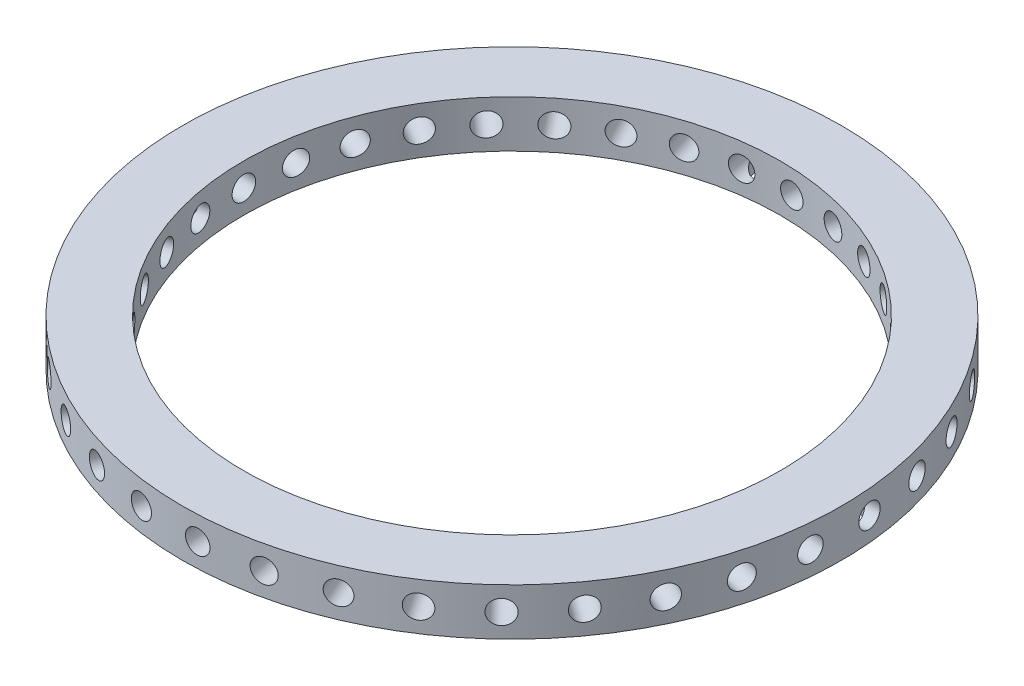
SolidWorks part; units mm, degrees
material "ABS"
ref_plane "Alzado" through (0, 0, 0) normal (0, 0, 1) x (1, 0, 0)
ref_plane "Planta" through (0, 0, 0) normal (0, 1, 0) x (1, 0, 0)
ref_plane "Vista lateral" through (0, 0, 0) normal (1, 0, 0) x (0, 0, -1)
sketch "Croquis1" plane through (0, 0, 0) normal (0, 0, 1) x (1, 0, 0)
  line L0 (0, 0) -> (-22.8, 0) construction
  line L1 (-22.8, 0) -> (-28, 0)
  line L2 (-28, 0) -> (-28, 1)
  line L3 (-28, 1) -> (-28, 4)
  line L4 (-22.8, 0) -> (-22.8, 4)
  line L5 (-22.8, 4) -> (-28, 4)
  line L6 (0, 0) -> (0, 7.1054) construction
  dimension "D1" = 22.8
  dimension "D2" = 28
  dimension "D3" = 1
  dimension "D4" = 3
revolve "Revolución1" add sketch "Croquis1" angle 360 about L6
ref_plane "Plano1" through (-28, 0, 0) normal (-1, 0, 0) x (0, 0, 1)
sketch "Croquis2" plane through (-28, 0, 0) normal (-1, 0, 0) x (0, 0, 1)
  line L2 (-28, 0) -> (28, 0) construction
  circle A0 centre (0, 2) radius 1
  dimension "D1" = 2
  dimension "D2" = 2
extrude "Cortar-Extruir1" cut sketch "Croquis2" along direction (-1, 0, 0) on the side against the normal blind 10
pattern_circular "MatrizC1" count 35 over 360 about axis through (0, 0, 0) along (0, -1, 0) of "Cortar-Extruir1"
sketch "Croquis3" plane through (0, 0, 0) normal (0, -1, 0) x (1, 0, 0)
  line L0 (-22.8, 0) -> (-22.3759, 4.3773) construction
  line L1 (-27.8695, 2.7004) -> (-26.8741, 2.6039) construction
  line L2 (-22.5879, 2.1886) -> (-27.8695, 2.7004) construction
  circle A0 centre (0, 0) radius 22.8 construction
  circle A1 centre (0, 0) radius 28 construction
  circle A2 centre (-25.0825, 2.4303) radius 1.8
  circle A3 centre (2.4303, 25.0825) radius 1.8
  circle A4 centre (25.0825, -2.4303) radius 1.8
  circle A5 centre (-2.4303, -25.0825) radius 1.8
  point P22 (0, 0)
  dimension "D1" = 1
  dimension "D2" = 3.6
  dimension "D3" = 4
extrude "Cortar-Extruir2" cut sketch "Croquis3" against normal blind 3.5
